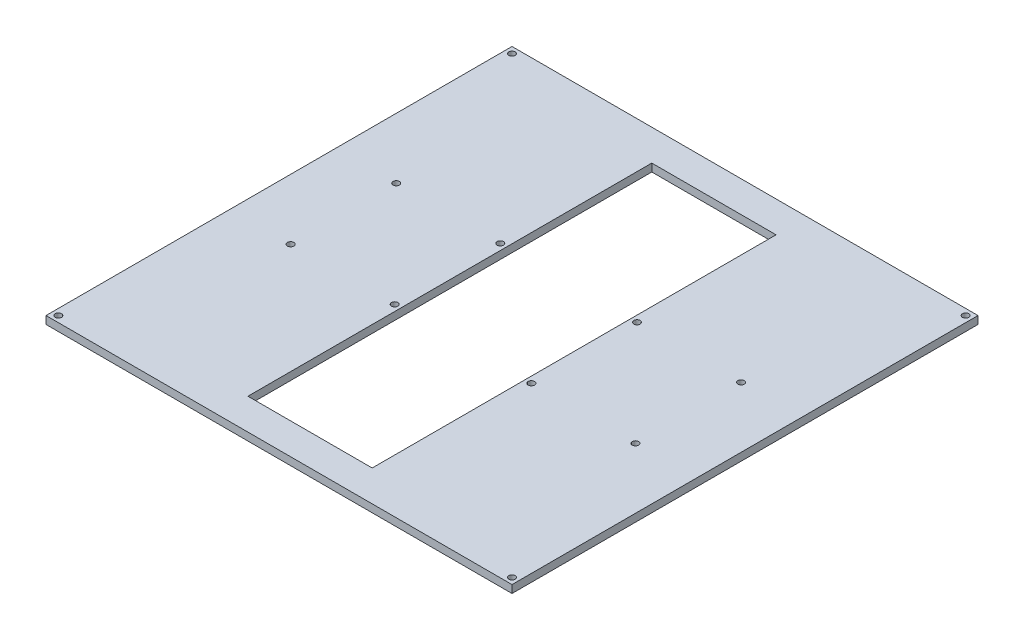
SolidWorks part; units mm, degrees
ref_plane "Front Plane" through (0, 0, 0) normal (0, 0, 1) x (1, 0, 0)
ref_plane "Top Plane" through (0, 0, 0) normal (0, 1, 0) x (1, 0, 0)
ref_plane "Right Plane" through (0, 0, 0) normal (1, 0, 0) x (0, 0, -1)
sketch "Sketch1" plane through (0, 0, 0) normal (0, 1, 0) x (1, 0, 0)
  line L1 (150, -150) -> (-150, -150)
  line L2 (150, -150) -> (150, 150)
  line L3 (150, 150) -> (-150, 150)
  line L4 (-150, -150) -> (-150, 150)
  line L5 (150, -150) -> (-150, 150) construction
  line L6 (150, 150) -> (-150, -150) construction
  point P0 (0, 0)
  dimension "D1" = 300
  dimension "D2" = 300
extrude "Boss-Extrude1" add sketch "Sketch1" along normal blind 5
sketch "Sketch2" plane through (0, 5, 0) normal (0, 1, 0) x (1, 0, 0)
  line L0 (150, 150) -> (-150, 150) construction
  line L2 (-150, 150) -> (-150, -150) construction
  line L3 (0, 0) -> (0, 49.0083) construction
  line L4 (0, 0) -> (-34.9845, 0) construction
  circle A0 centre (-146, 146) radius 2.05
  dimension "D3" = 4.1
  dimension "D1" = 4
  dimension "D2" = 4
extrude "Cut-Extrude1" cut sketch "Sketch2" against normal up to next
mirror "Mirror1" about plane through (0, 0, 0) normal (1, 0, 0) of "Cut-Extrude1" second plane through (0, 0, 0) second plane normal (0, 0, 1)
sketch "Sketch3" plane through (0, 5, 0) normal (0, 1, 0) x (1, 0, 0)
  line L1 (40, -130) -> (-40, -130)
  line L2 (40, -130) -> (40, 130)
  line L3 (40, 130) -> (-40, 130)
  line L4 (-40, -130) -> (-40, 130)
  line L5 (40, -130) -> (-40, 130) construction
  line L6 (40, 130) -> (-40, -130) construction
  point P0 (0, 0)
  dimension "D1" = 80
  dimension "D2" = 260
extrude "Cut-Extrude2" cut sketch "Sketch3" against normal up to next
sketch "Sketch4" plane through (0, 5, 0) normal (0, 1, 0) x (1, 0, 0)
  line L0 (-44, -31.5315) -> (-111, -31.5315) construction
  line L1 (-44, -31.5315) -> (-44, 36.4685) construction
  line L2 (-44, 36.4685) -> (-111, 36.4685) construction
  line L3 (-111, -31.5315) -> (-111, 36.4685) construction
  line L4 (-44, -31.5315) -> (-111, 36.4685) construction
  line L5 (-44, 36.4685) -> (-111, -31.5315) construction
  line L7 (-40, 130) -> (-40, -130) construction
  circle A0 centre (-111, 36.4685) radius 2.05
  circle A1 centre (-44, 36.4685) radius 2.05
  circle A2 centre (-44, -31.5315) radius 2.05
  circle A3 centre (-111, -31.5315) radius 2.05
  point P0 (-77.5, 2.4685)
  dimension "D4" = 4.1
  dimension "D1" = 67
  dimension "D2" = 68
  dimension "D3" = 4
extrude "Cut-Extrude3" cut sketch "Sketch4" against normal up to next
mirror "Mirror2" about plane through (0, 0, 0) normal (1, 0, 0) of "Cut-Extrude3"
